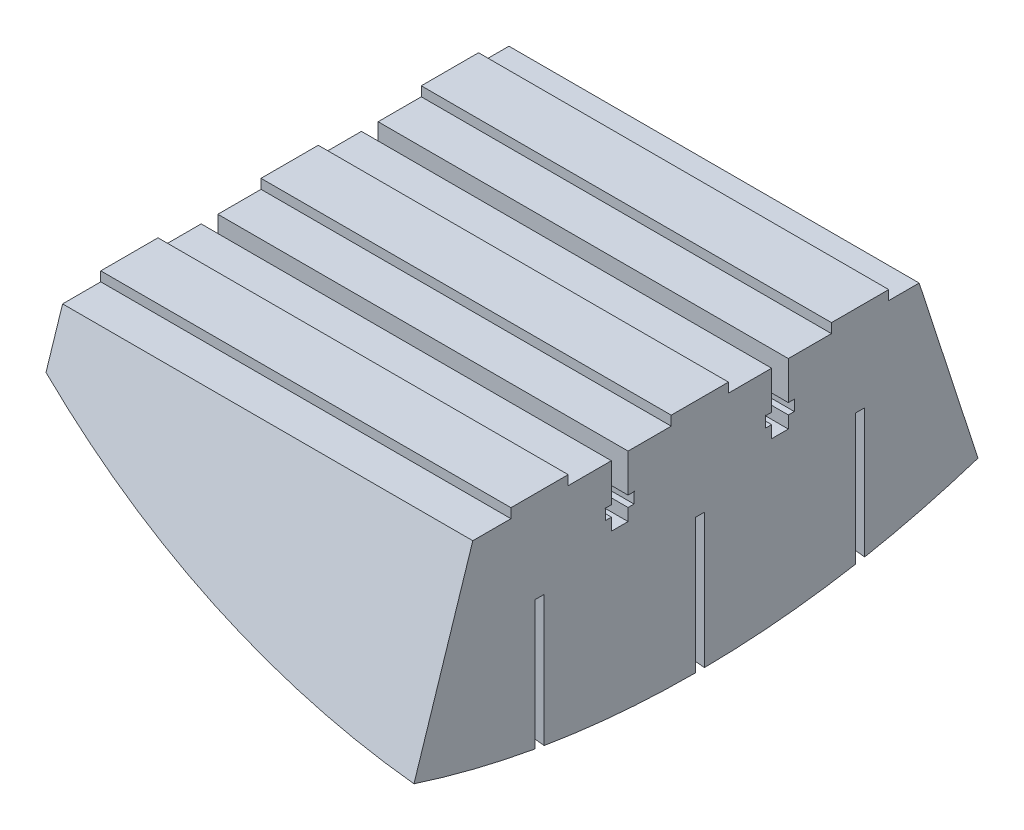
SolidWorks part; units mm, degrees
ref_plane "Front Plane" through (0, 0, 0) normal (0, 0, 1) x (1, 0, 0)
ref_plane "Top Plane" through (0, 0, 0) normal (0, 1, 0) x (1, 0, 0)
ref_plane "Right Plane" through (0, 0, 0) normal (1, 0, 0) x (0, 0, -1)
sketch "Sketch1" plane through (0, 0, 0) normal (0, 0, 1) x (1, 0, 0)
  line L0 (0, 0) -> (0, 125.3059) construction
  line L1 (0, 0) -> (-289.7399, 0) construction
  line L2 (-202.802, -227.5398) -> (-25.4, -227.5398)
  line L3 (-25.4, -227.5398) -> (-25.4, -303.7398)
  arc A0 (-25.4, -303.7398) -> (-202.802, -227.5398) centre (0, 0) cw
  dimension "D1" = 304.8
  dimension "D2" = 25.4
  dimension "D3" = 76.2
revolve "Revolve1" add sketch "Sketch1" angle 36 mid plane about L1
sketch "Sketch2" plane through (-25.4, 0, 0) normal (1, 0, 0) x (0, 0, -1)
  line L1 (-89.4432, -172.2284) -> (95.809, -172.2284)
  line L2 (-89.4432, -172.2284) -> (-89.4432, -228.6)
  line L3 (-89.4432, -228.6) -> (95.809, -228.6)
  line L4 (95.809, -172.2284) -> (95.809, -228.6)
  arc A0 (-70.3137, -216.4032) -> (70.3137, -216.4032) centre (0, 0) ccw construction
  dimension "D1" = 228.6
extrude "Cut-Extrude1" cut sketch "Sketch2" against normal through all
sketch "Sketch5" plane through (0, -228.6, 0) normal (0, 1, 0) x (1, 0, 0)
  line L0 (-187.4248, -74.2766) -> (-187.4248, 74.2766)
  line L1 (-187.4248, -74.2766) -> (-243.0799, -74.2766)
  line L2 (-187.4248, 74.2766) -> (-243.0799, 74.2766)
  line L3 (-243.0799, -74.2766) -> (-243.0799, 74.2766)
extrude "Cut-Extrude2" cut sketch "Sketch5" against normal through all
sketch "Sketch6" plane through (0, -228.6, 0) normal (0, 1, 0) x (1, 0, 0)
  line L0 (-187.4248, -74.2766) -> (-187.4248, 74.2766) construction
  line L1 (-25.4, -61.5766) -> (-187.4248, -61.5766)
  line L2 (-25.4, -61.5766) -> (-25.4, -42.5266)
  line L3 (-25.4, -42.5266) -> (-187.4248, -42.5266)
  line L4 (-187.4248, -61.5766) -> (-187.4248, -42.5266)
  line L5 (-25.4, -74.2766) -> (-187.4248, -74.2766) construction
  dimension "D1" = 19.05
  dimension "D2" = 12.7
extrude "Boss-Extrude1" add sketch "Sketch6" along normal blind 3.175
pattern_linear "LPattern1" count 3 spacing 53.34 along (0, 0, -1) of "Boss-Extrude1"
sketch "Sketch7" plane through (-25.4, 0, 0) normal (1, 0, 0) x (0, 0, -1)
  line L0 (-22.6035, -244.856) -> (-22.6035, -248.92)
  line L1 (-42.5266, -228.6) -> (-8.2366, -228.6) construction
  line L2 (-22.6035, -228.6) -> (-28.1598, -228.6)
  line L3 (-28.1598, -228.6) -> (-28.1598, -241.3)
  line L4 (-28.1598, -241.3) -> (-30.0171, -241.3)
  line L5 (-30.1441, -241.427) -> (-30.1441, -244.856)
  line L6 (-30.1441, -244.856) -> (-28.1598, -244.856)
  line L7 (-28.1598, -244.856) -> (-28.1598, -248.92)
  line L8 (-28.1598, -248.92) -> (-22.6035, -248.92)
  line L9 (-25.3816, -228.6) -> (-25.3816, -263.1045) construction
  line L10 (-20.6191, -244.856) -> (-22.6035, -244.856)
  line L11 (-20.6191, -241.427) -> (-20.6191, -244.856)
  line L12 (-22.6035, -241.3) -> (-20.7461, -241.3)
  line L13 (-22.6035, -228.6) -> (-22.6035, -241.3)
  arc A0 (-30.0171, -241.3) -> (-30.1441, -241.427) centre (-30.1441, -241.3) ccw
  arc A1 (-20.7461, -241.3) -> (-20.6191, -241.427) centre (-20.6191, -241.3) cw
  point P0 (-25.3816, -228.6)
  point P18 (-25.3816, -248.92)
  dimension "D4" = 2.7781
  dimension "D3" = 0.127
  dimension "D1" = 20.32
  dimension "D2" = 3.429
  dimension "D5" = 9.525
  dimension "D6" = 12.7
extrude "Cut-Extrude3" cut sketch "Sketch7" against normal through all
pattern_linear "LPattern2" count 2 spacing 53.34 along (0, 0, -1) of "Cut-Extrude3"
sketch "Sketch8" plane through (0, -225.425, 0) normal (0, 1, 0) x (1, 0, 0)
  line L0 (-25.4, -8.2366) -> (-25.4, 10.8134) construction
  line L1 (-215.6308, 85.3843) -> (-161.925, 85.3843)
  line L2 (-215.6308, 85.3843) -> (-215.6308, -110.6191)
  line L3 (-215.6308, -110.6191) -> (-161.925, -110.6191)
  line L4 (-161.925, 85.3843) -> (-161.925, -110.6191)
  dimension "D1" = 136.525
extrude "Cut-Extrude4" cut sketch "Sketch8" against normal through all
ref_plane "Plane1" through (-38.1, 0, 0) normal (1, 0, 0) x (0, 0, -1)
ref_plane "Plane2" through (-50.8, 0, 0) normal (1, 0, 0) x (0, 0, -1)
ref_plane "Plane3" through (-63.5, 0, 0) normal (1, 0, 0) x (0, 0, -1)
ref_plane "Plane4" through (-76.2, 0, 0) normal (1, 0, 0) x (0, 0, -1)
ref_plane "Plane5" through (-88.9, 0, 0) normal (1, 0, 0) x (0, 0, -1)
ref_plane "Plane6" through (-101.6, 0, 0) normal (1, 0, 0) x (0, 0, -1)
ref_plane "Plane7" through (-114.3, 0, 0) normal (1, 0, 0) x (0, 0, -1)
ref_plane "Plane8" through (-127, 0, 0) normal (1, 0, 0) x (0, 0, -1)
ref_plane "Plane9" through (-139.7, 0, 0) normal (1, 0, 0) x (0, 0, -1)
ref_plane "Plane10" through (-152.4, 0, 0) normal (1, 0, 0) x (0, 0, -1)
sketch "Sketch9" plane through (-25.4, 0, 0) normal (1, 0, 0) x (0, 0, -1)
  line L0 (-52.0516, -225.425) -> (-52.0516, -299.2466) construction
  line L1 (-61.5766, -225.425) -> (-42.5266, -225.425) construction
  line L2 (1.2884, -225.425) -> (1.2884, -303.7371) construction
  line L3 (-8.2366, -225.425) -> (10.8134, -225.425) construction
  line L4 (54.6284, -225.425) -> (54.6284, -298.7869) construction
  line L5 (45.1034, -225.425) -> (64.1534, -225.425) construction
  line L7 (-50.5276, -342.5557) -> (-53.5756, -342.5557)
  line L8 (-50.5276, -342.5557) -> (-50.5276, -255.9374)
  line L9 (-50.5276, -255.9374) -> (-53.5756, -255.9374)
  line L10 (-53.5756, -342.5557) -> (-53.5756, -255.9374)
  line L11 (-50.5276, -342.5557) -> (-53.5756, -255.9374) construction
  line L12 (-50.5276, -255.9374) -> (-53.5756, -342.5557) construction
  line L13 (2.8124, -348.5626) -> (-0.2356, -348.5626)
  line L14 (2.8124, -348.5626) -> (2.8124, -258.9116)
  line L15 (2.8124, -258.9116) -> (-0.2356, -258.9116)
  line L16 (-0.2356, -348.5626) -> (-0.2356, -258.9116)
  line L17 (2.8124, -348.5626) -> (-0.2356, -258.9116) construction
  line L18 (2.8124, -258.9116) -> (-0.2356, -348.5626) construction
  line L19 (56.1524, -342.0961) -> (53.1044, -342.0961)
  line L20 (56.1524, -342.0961) -> (56.1524, -255.4777)
  line L21 (56.1524, -255.4777) -> (53.1044, -255.4777)
  line L22 (53.1044, -342.0961) -> (53.1044, -255.4777)
  line L23 (56.1524, -342.0961) -> (53.1044, -255.4777) construction
  line L24 (56.1524, -255.4777) -> (53.1044, -342.0961) construction
  arc A0 (-93.8608, -288.8737) -> (93.8608, -288.8737) centre (0, 0) ccw construction
  dimension "D1" = 3.048
sketch "Sketch10" plane through (0, 0, 0) normal (1, 0, 0) x (0, 0, -1)
  line L4 (53.1044, -342.0961) -> (56.1524, -342.0961)
  line L5 (53.1044, -255.4777) -> (53.1044, -342.0961)
  line L6 (56.1524, -255.4777) -> (53.1044, -255.4777)
  line L7 (56.1524, -342.0961) -> (56.1524, -255.4777)
  line L8 (53.1044, -342.0961) -> (56.1524, -342.0961)
  line L9 (53.1044, -255.4777) -> (53.1044, -342.0961)
  line L10 (56.1524, -255.4777) -> (53.1044, -255.4777)
  line L11 (56.1524, -342.0961) -> (56.1524, -255.4777)
  line L12 (-0.2356, -348.5626) -> (2.8124, -348.5626)
  line L13 (-0.2356, -258.9116) -> (-0.2356, -348.5626)
  line L14 (2.8124, -258.9116) -> (-0.2356, -258.9116)
  line L15 (2.8124, -348.5626) -> (2.8124, -258.9116)
  line L16 (-0.2356, -348.5626) -> (2.8124, -348.5626)
  line L17 (-0.2356, -258.9116) -> (-0.2356, -348.5626)
  line L18 (2.8124, -258.9116) -> (-0.2356, -258.9116)
  line L19 (2.8124, -348.5626) -> (2.8124, -258.9116)
  line L20 (-53.5756, -342.5557) -> (-50.5276, -342.5557)
  line L21 (-53.5756, -255.9374) -> (-53.5756, -342.5557)
  line L22 (-50.5276, -255.9374) -> (-53.5756, -255.9374)
  line L23 (-50.5276, -342.5557) -> (-50.5276, -255.9374)
  line L24 (-53.5756, -342.5557) -> (-50.5276, -342.5557)
  line L25 (-53.5756, -255.9374) -> (-53.5756, -342.5557)
  line L26 (-50.5276, -255.9374) -> (-53.5756, -255.9374)
  line L27 (-50.5276, -342.5557) -> (-50.5276, -255.9374)
  dimension "D1" = 0
  dimension "D2" = 0
  dimension "D3" = 0
extrude "Cut-Extrude6" cut sketch "Sketch10" against normal blind 176.53
sketch "Sketch17" plane through (0, 0, 50.5276) normal (0, 0, 1) x (1, 0, 0)
  line L0 (-25.4, -299.5077) -> (-25.4, -255.9374)
  line L1 (-157.6263, -255.9374) -> (-25.4, -255.9374)
  arc A3 (-157.6263, -255.9374) -> (-25.4, -299.5077) centre (0, 0) ccw construction
  spline S0 degree 3 poles (-157.6263, -255.9374) (-115.7161, -281.0628) (-71.6406, -295.5862) (-25.4, -299.5077) knots 0 0 0 0 1 1 1 1
sketch "Sketch18" plane through (0, 0, -2.8124) normal (0, 0, 1) x (1, 0, 0)
  line L0 (-25.4, -303.7268) -> (-25.4, -258.9116)
  line L1 (-25.4, -258.9116) -> (-160.8103, -258.9116)
  arc A0 (-160.8103, -258.9116) -> (-25.4, -303.7268) centre (0, 0) ccw construction
  spline S0 degree 2 poles (-25.4, -303.7268) (-96.4687, -297.7835) (-160.8103, -258.9116) knots 0 0 0 1 1 1
